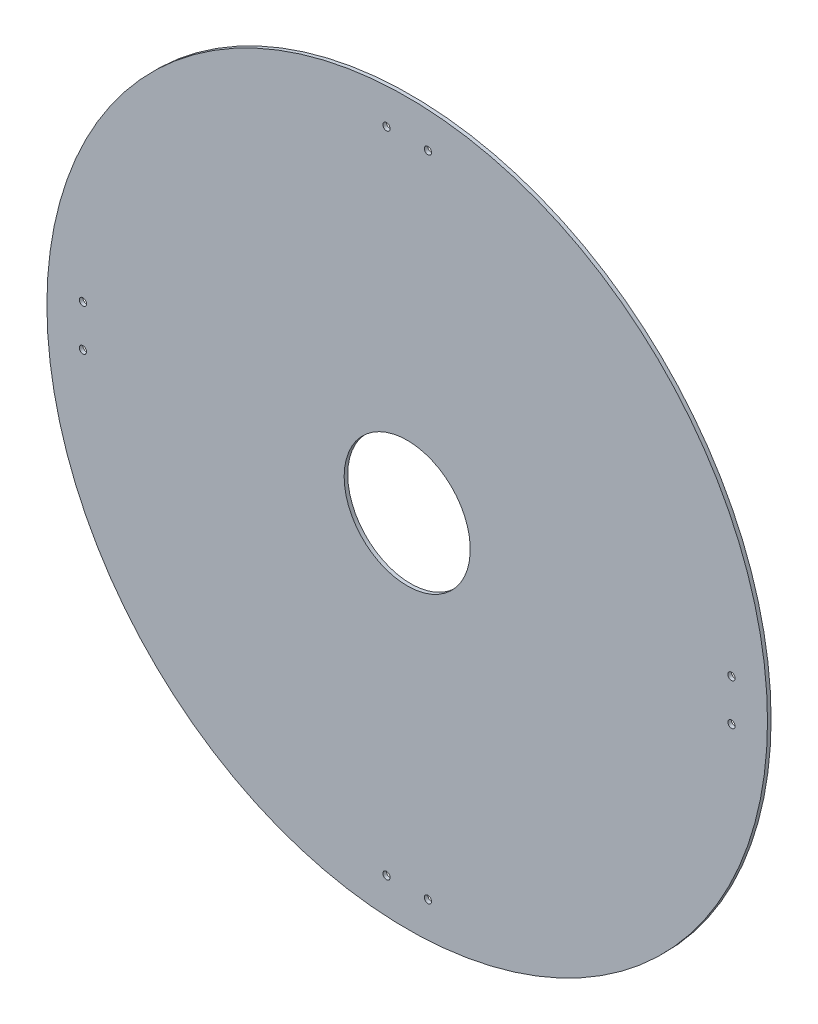
SolidWorks part; units mm, degrees
ref_plane "Front Plane" through (0, 0, 0) normal (0, 0, 1) x (1, 0, 0)
ref_plane "Top Plane" through (0, 0, 0) normal (0, 1, 0) x (1, 0, 0)
ref_plane "Right Plane" through (0, 0, 0) normal (1, 0, 0) x (0, 0, -1)
sketch "Sketch1" plane through (0, 0, 0) normal (0, 0, 1) x (1, 0, 0)
  circle A0 centre (0, 0) radius 200
  dimension "D1" = 400
extrude "Boss-Extrude1" add sketch "Sketch1" along normal blind 2
sketch "Sketch2" plane through (0, 0, 0) normal (0, 0, -1) x (-1, 0, 0)
  line L0 (0, 0) -> (0, 200) construction
  line L1 (-11.5, 180) -> (11.5, 180) construction
  circle A0 centre (0, 0) radius 200 construction
  circle A1 centre (11.5, 180) radius 2
  circle A2 centre (-11.5, 180) radius 2
  point P9 (0, 180)
  dimension "D2" = 4
  dimension "D1" = 23
  dimension "D3" = 180
extrude "Cut-Extrude1" cut sketch "Sketch2" against normal blind 13
pattern_circular "CirPattern1" count 4 over 360 about axis through (0, 0, 0) along (0, 0, 1) of "Cut-Extrude1"
sketch "Sketch4" plane through (0, 0, 0) normal (0, 0, -1) x (-1, 0, 0)
  circle A0 centre (0, 0) radius 35
  dimension "D1" = 70
extrude "Cut-Extrude3" cut sketch "Sketch4" against normal through all
